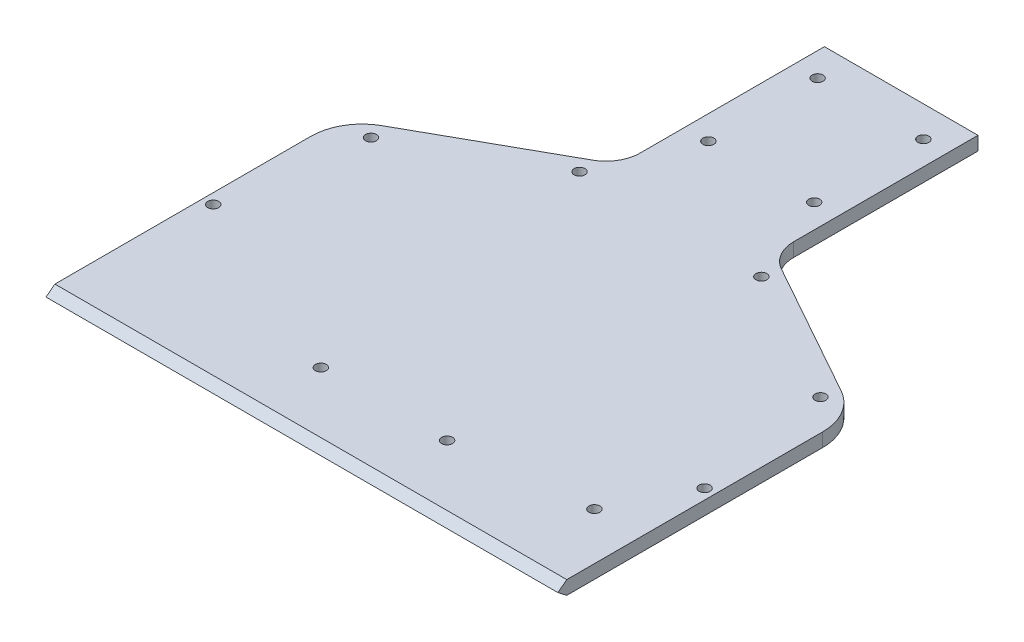
SolidWorks part; units mm, degrees
ref_plane "Plan de face" through (0, 0, 0) normal (0, 0, 1) x (1, 0, 0)
ref_plane "Plan de dessus" through (0, 0, 0) normal (0, 1, 0) x (1, 0, 0)
ref_plane "Plan de droite" through (0, 0, 0) normal (1, 0, 0) x (0, 0, -1)
sketch "Esquisse1" plane through (0, 0, 0) normal (0, -1, 0) x (1, 0, 0)
  line L0 (22.5, 171.3) -> (22.5, 117.3)
  line L1 (28.9241, 107.9612) -> (65.3638, 94.0082)
  line L2 (75, 80) -> (75, -80)
  line L3 (67.3157, -93.095) -> (27.6229, -115.27)
  line L4 (22.5, -124) -> (22.5, -178)
  line L14 (22.5, 171.3) -> (-22.5, 171.3)
  line L18 (0, 171.3) -> (0, -178) construction
  line L20 (-22.5, -178) -> (22.5, -178)
  line L22 (-22.5, -124) -> (-22.5, -178)
  line L23 (-67.3157, -93.095) -> (-27.6229, -115.27)
  line L25 (-75, 80) -> (-75, -80)
  line L26 (-28.9241, 107.9612) -> (-65.3638, 94.0082)
  line L27 (-22.5, 171.3) -> (-22.5, 117.3)
  arc A0 (28.9241, 107.9612) -> (22.5, 117.3) centre (32.5, 117.3) cw
  arc A1 (65.3638, 94.0082) -> (75, 80) centre (60, 80) cw
  arc A2 (75, -80) -> (67.3157, -93.095) centre (60, -80) cw
  arc A3 (22.5, -124) -> (27.6229, -115.27) centre (32.5, -124) cw
  arc A12 (-22.5, -124) -> (-27.6229, -115.27) centre (-32.5, -124) ccw
  arc A13 (-75, -80) -> (-67.3157, -93.095) centre (-60, -80) ccw
  arc A14 (-65.3638, 94.0082) -> (-75, 80) centre (-60, 80) ccw
  arc A15 (-28.9241, 107.9612) -> (-22.5, 117.3) centre (-32.5, 117.3) ccw
  point P18 (0, -178)
  point P19 (0, 171.3)
  point P36 (-75, 0)
  dimension "D7" = 15
  dimension "D8" = 10
  dimension "D1" = 150
  dimension "D2" = 45
  dimension "D3" = 349.3
  dimension "D4" = 54
  dimension "D5" = 54
  dimension "D6" = 44
  dimension "D9" = 178
  dimension "D10" = 75
extrude "Boss.-Extru.1" add sketch "Esquisse1" along normal blind 4
hole_wizard "Fraisage pour vis à tête fraisée M31" positions "Esquisse3" profile "Esquisse2" countersink size "M3" standard "Ansi Metric" end condition up to next
sketch "Esquisse3" plane through (0, -4, 0) normal (0, -1, 0) x (-1, 0, 0)
  line L0 (-75, 80) -> (-75, -80) construction
  line L1 (22.5, 124) -> (22.5, 178) construction
  line L2 (22.5, 178) -> (-22.5, 178) construction
  line L3 (-22.5, 178) -> (-22.5, 124) construction
  line L4 (-75, 80) -> (-75, -80) construction
  point P0 (14.85, -9.22)
  point P3 (-22.15, -9.22)
  point P6 (-61.15, -3.06)
  point P9 (-61.15, 26.94)
  point P12 (-22.15, 22.78)
  point P15 (14.85, 22.78)
  point P18 (15.5, 137)
  point P21 (-15.5, 137)
  point P24 (15.5, 169)
  point P27 (-15.5, 169)
  point P30 (63.0257, -89.6123)
  point P32 (72, -51.7763)
  point P34 (72, 48.3763)
  point P36 (65.8526, 88.476)
  point P38 (26.643, 110.381)
  point P40 (-26.643, 110.381)
  point P42 (-65.8526, 88.476)
  point P44 (-72, 48.3763)
  point P46 (-63.0257, -89.6123)
  point P48 (-72, -51.7763)
  point P49 (20, -81.3983)
  point P51 (-20, -81.3983)
  point P59 (-72, -1.7)
  point P61 (72, -1.7)
  point P67 (-55, -68.06)
  point P71 (-55, -18.06)
  dimension "D1" = 13.85
  dimension "D2" = 15
  dimension "D3" = 30
  dimension "D4" = 32
  dimension "D5" = 37
  dimension "D6" = 39
  dimension "D7" = 6.16
  dimension "D8" = 7
  dimension "D9" = 32
  dimension "D10" = 9
  dimension "D11" = 7
  dimension "D12" = 22.78
  dimension "D13" = 50
  dimension "D14" = 20
sketch "Esquisse2" plane through (-14.85, -4, 9.22) normal (1, 0, 0) x (0, 0, -1)
  line L0 (0, 0) -> (0, 4)
  line L1 (0, 4) -> (1.6, 4)
  line L2 (1.6, 4) -> (1.6, 1.7)
  line L3 (1.6, 1.7) -> (2.9, 0.4)
  line L4 (2.9, 0.4) -> (2.9, 0)
  line L6 (2.9, 0) -> (0, 0)
  line L7 (-1.6, 1.7) -> (-2.9, 0.4) construction
  line L11 (0, -6.35) -> (0, 107.95) construction
  dimension "Diamètre du perçage jusqu'au prochain" = 3.2
  dimension "Profondeur du perçage jusqu'au prochain" = 4
  dimension "Diamètre du fraisage" = 5.8
  dimension "Angle du fraisage" = 90
  dimension "Dégagement de la tête" = 0.4
ref_plane "Plan1" through (15.5, 0, 0) normal (1, 0, 0) x (0, 0, -1)
sketch "Esquisse4" plane through (15.5, 0, 0) normal (1, 0, 0) x (0, 0, -1)
  line L0 (-130.4423, 1.9719) -> (-128.8511, 1.8047)
  line L1 (-133.8804, -2.9959) -> (-128.1122, -3.6022) construction
  line L2 (-128.8511, 1.8047) -> (-129.2692, -2.1734)
  line L3 (-129.2692, -2.1734) -> (-128.1122, -3.6022)
  line L4 (-128.1122, -3.6022) -> (-128.2177, -4.6063)
  line L5 (-133.9223, -3.3937) -> (-128.154, -4) construction
  line L6 (-130.4423, 1.9719) -> (-131.1019, -4.3031)
  line L7 (-131.1019, -4.3031) -> (-128.2177, -4.6063)
  line L8 (-171.3, -4) -> (-171.3, 0) construction
  line L10 (-131.1019, -4.3031) -> (-133.986, -4) construction
  line L12 (-117.3, -4) -> (-171.3, -4) construction
  line L13 (-133.986, -4) -> (-133.8804, -2.9959) construction
  line L14 (-133.8804, -2.9959) -> (-130.6932, -0.4149) construction
  line L15 (-129.2692, -2.1734) -> (-130.6932, -0.4149) construction
  point P19 (-131.07, -4)
  dimension "D1" = 90
  dimension "D2" = 5.8
  dimension "D3" = 0.4
  dimension "D4" = 1.6
  dimension "D5" = 4
  dimension "D6" = 84
  dimension "D7" = 40.23
revolve "Enlèvement de matière-Révolution1" cut sketch "Esquisse4" angle 360 about L6
sketch "Esquisse6" plane through (15.5, 0, 0) normal (1, 0, 0) x (0, 0, -1)
  line L0 (-162.8258, 0) -> (-163.2463, -4) construction
  line L1 (-117.3, -4) -> (-171.3, -4) construction
  line L2 (-117.3, 0) -> (-171.3, 0) construction
  line L5 (-130.6496, 0) -> (-131.07, -4) construction
  dimension "D1" = 84
  dimension "D2" = 32
sketch "Esquisse5" plane through (15.5, 0, 0) normal (1, 0, 0) x (0, 0, -1)
  line L0 (-162.7555, 0.6689) -> (-161.1643, 0.5017)
  line L1 (-161.1643, 0.5017) -> (-161.4453, -2.1714)
  line L2 (-161.4453, -2.1714) -> (-160.2849, -3.6026)
  line L3 (-160.2849, -3.6026) -> (-160.3302, -4)
  line L4 (-160.3302, -4) -> (-160.3993, -4.6063)
  line L5 (-160.3993, -4.6063) -> (-163.2782, -4.3037)
  line L6 (-163.2782, -4.3037) -> (-166.1677, -4) construction
  line L7 (-166.1677, -4) -> (-166.0986, -3.3937) construction
  line L8 (-166.0533, -2.9963) -> (-162.8694, -0.4148) construction
  line L9 (-162.7555, 0.6689) -> (-163.2782, -4.3037)
  line L10 (-166.0986, -3.3937) -> (-166.0533, -2.9963) construction
  line L11 (-160.3302, -4) -> (-166.0986, -3.3937) construction
  line L12 (-162.8258, 0) -> (-163.2463, -4) construction
  line L13 (-171.3, -4) -> (-117.3, -4) construction
  line L14 (-157.2606, -6.1647) -> (-155.7772, 6.8554) construction
  line L16 (-117.3, -4) -> (-171.3, -4) construction
  line L17 (-161.4453, -2.1714) -> (-162.8694, -0.4148) construction
  point P11 (-163.2144, -3.6969)
  point P20 (-163.2463, -4)
  dimension "D1" = 5.8
  dimension "D2" = 0.4
  dimension "D3" = 90
  dimension "D4" = 1.6
  dimension "D6" = 5
revolve "Enlèvement de matière-Révolution2" cut sketch "Esquisse5" angle 360 about L9
mirror "Symétrie1" about plane through (0, 0, 0) normal (1, 0, 0) of "Enlèvement de matière-Révolution2", "Enlèvement de matière-Révolution1"
sketch "Esquisse7" plane through (0, 0, 0) normal (1, 0, 0) x (0, 0, -1)
  line L0 (80, 0) -> (-80, 0) construction
  line L1 (5, 0) -> (-171.3, 0)
  line L2 (5, 0) -> (5, -4)
  line L3 (5, -4) -> (-171.3, -4)
  line L4 (-171.3, 0) -> (-171.3, -4)
  dimension "D1" = 5
extrude "Enlèv. mat.-Extru.1" cut sketch "Esquisse7" against normal up to next and the other way up to next
sketch "Esquisse8" plane through (75, 0, 0) normal (1, 0, 0) x (0, 0, -1)
  line L0 (5, 0) -> (2.3935, -2)
  line L1 (2.3935, -2) -> (5, -4)
  line L2 (5, -4) -> (5, 0)
  line L3 (0, 0) -> (0, -4) construction
  line L4 (0, -2) -> (5, -2) construction
  point P11 (0, -4)
  point P12 (0, -4)
  point P13 (1.5066, -2)
  dimension "D1" = 75
extrude "Boss.-Extru.2" add sketch "Esquisse8" against normal up to surface (150 mm away) up to face at (-75, -2, -42.5)
